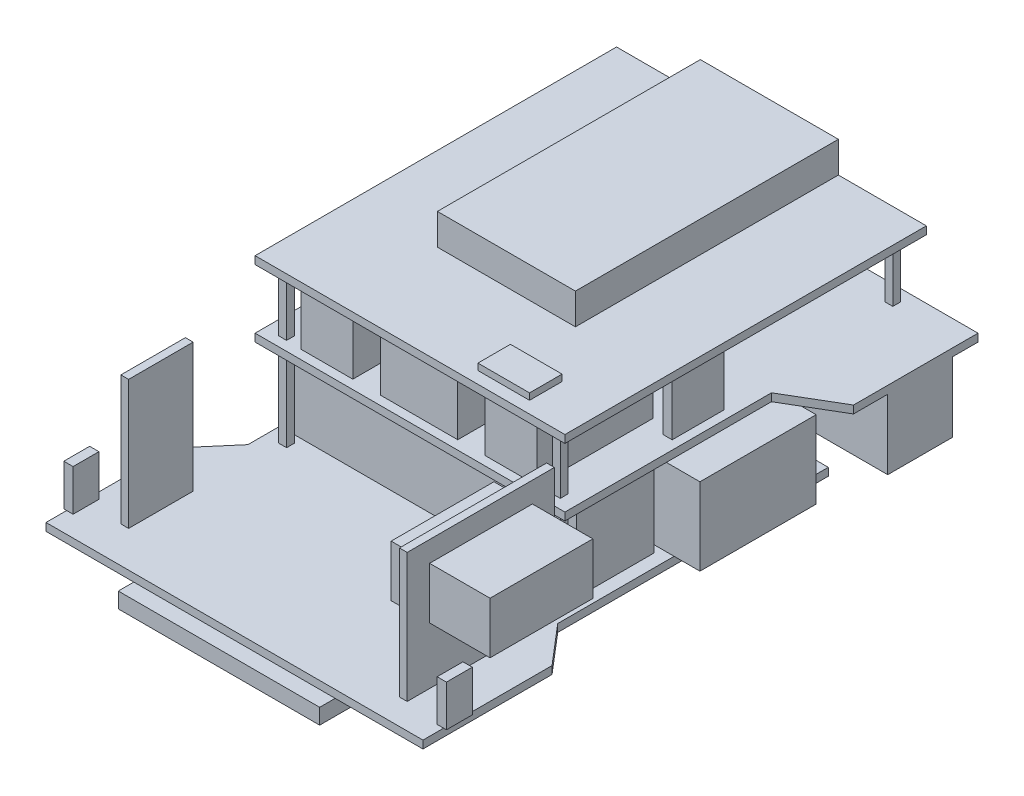
SolidWorks part; units mm, degrees
ref_plane "Front Plane" through (0, 0, 0) normal (0, 0, 1) x (1, 0, 0)
ref_plane "Top Plane" through (0, 0, 0) normal (0, 1, 0) x (1, 0, 0)
ref_plane "Right Plane" through (0, 0, 0) normal (1, 0, 0) x (0, 0, -1)
sketch "Sketch1" plane through (0, 0, 0) normal (0, 1, 0) x (1, 0, 0)
  line L0 (-73, -35) -> (-60, -19.8013)
  line L1 (60, -85) -> (-60, -85)
  line L2 (60, -19.8013) -> (60, 85)
  line L3 (60, 85) -> (-60, 85)
  line L4 (-60, -19.8013) -> (-60, 85)
  line L5 (60, -85) -> (-60, 85) construction
  line L6 (60, 85) -> (-60, -85) construction
  line L7 (0, 0) -> (0, -85) construction
  line L9 (-60, -85) -> (-73, -85)
  line L10 (-73, -35) -> (-73, -85)
  line L11 (60, -85) -> (73, -85)
  line L12 (73, -35) -> (73, -85)
  line L13 (73, -35) -> (60, -19.8013)
  point P0 (0, 0)
  dimension "D1" = 170
  dimension "D2" = 120
  dimension "D3" = 50
  dimension "D4" = 13
  dimension "D5" = 20
extrude "Boss-Extrude1" add sketch "Sketch1" along normal blind 3
sketch "Sketch2" plane through (0, 3, 0) normal (0, 1, 0) x (1, 0, 0)
  line L0 (0, 0) -> (0, 85) construction
  line L1 (60, 85) -> (-60, 85) construction
  line L2 (-60, 85) -> (-60, -19.8013) construction
  line L4 (-54.525, -13.335) -> (-51.475, -13.335)
  line L5 (-54.525, -13.335) -> (-54.525, -10.285)
  line L6 (-54.525, -10.285) -> (-51.475, -10.285)
  line L7 (-51.475, -13.335) -> (-51.475, -10.285)
  line L8 (-54.525, -13.335) -> (-51.475, -10.285) construction
  line L9 (-54.525, -10.285) -> (-51.475, -13.335) construction
  line L10 (51.475, -13.335) -> (54.525, -13.335)
  line L11 (51.475, -13.335) -> (51.475, -10.285)
  line L12 (51.475, -10.285) -> (54.525, -10.285)
  line L13 (54.525, -13.335) -> (54.525, -10.285)
  line L14 (51.475, -13.335) -> (54.525, -10.285) construction
  line L15 (51.475, -10.285) -> (54.525, -13.335) construction
  line L16 (52.475, 73.475) -> (55.525, 73.475)
  line L17 (52.475, 73.475) -> (52.475, 76.525)
  line L18 (52.475, 76.525) -> (55.525, 76.525)
  line L19 (55.525, 73.475) -> (55.525, 76.525)
  line L20 (52.475, 73.475) -> (55.525, 76.525) construction
  line L21 (52.475, 76.525) -> (55.525, 73.475) construction
  line L22 (-55.525, 73.475) -> (-52.475, 73.475)
  line L23 (-55.525, 73.475) -> (-55.525, 76.525)
  line L24 (-55.525, 76.525) -> (-52.475, 76.525)
  line L25 (-52.475, 73.475) -> (-52.475, 76.525)
  line L26 (-55.525, 73.475) -> (-52.475, 76.525) construction
  line L27 (-55.525, 76.525) -> (-52.475, 73.475) construction
  circle A0 centre (-53, -11.81) radius 1.525 construction
  circle A1 centre (-54, 75) radius 1.525 construction
  circle A2 centre (53, -11.81) radius 1.525 construction
  circle A3 centre (54, 75) radius 1.525 construction
  dimension "D1" = 10
  dimension "D2" = 3.05
  dimension "D3" = 6
  dimension "D4" = 3.05
  dimension "D5" = 7
  dimension "D6" = 86.81
extrude "Boss-Extrude2" add sketch "Sketch2" along normal blind 33
sketch "Sketch3" plane through (0, 36, 0) normal (0, 1, 0) x (1, 0, 0)
  line L0 (0, 52.99) -> (0, 122.99) construction
  line L1 (-60, -17.01) -> (60, -17.01)
  line L2 (-60, -17.01) -> (-60, 122.99)
  line L3 (-60, 122.99) -> (60, 122.99)
  line L4 (60, -17.01) -> (60, 122.99)
  line L5 (-60, -17.01) -> (60, 122.99) construction
  line L6 (-60, 122.99) -> (60, -17.01) construction
  line L7 (-60, 122.99) -> (-80, 122.99)
  line L8 (-80, 122.99) -> (-80, 74.7803)
  line L9 (-80, 74.7803) -> (-60, 62.99)
  line L10 (80, 74.7803) -> (60, 62.99)
  line L11 (80, 122.99) -> (80, 74.7803)
  line L12 (60, 122.99) -> (80, 122.99)
  line L14 (-54.525, -10.285) -> (-54.525, -13.335) construction
  point P0 (0, 52.99)
  point P5 (0, 0)
  point P15 (-80, 45.2902)
  point P16 (0, 0)
  point P19 (-54.525, -11.81)
  dimension "D1" = 120
  dimension "D2" = 140
  dimension "D3" = 60
  dimension "D4" = 30.52
  dimension "D5" = 20
  dimension "D6" = 5.2
extrude "Boss-Extrude3" add sketch "Sketch3" along normal blind 3 contours L8 L9 L2 L7 | L1 L4 L3 L2 | L12 L4 L10 L11
sketch "Sketch4" plane through (0, 39, 0) normal (0, 1, 0) x (1, 0, 0)
  line L0 (0, 0) -> (0, 32.3428) construction
  line L1 (-54.525, -13.335) -> (-51.475, -13.335)
  line L2 (-54.525, -13.335) -> (-54.525, -10.285)
  line L3 (-54.525, -10.285) -> (-51.475, -10.285)
  line L4 (-51.475, -13.335) -> (-51.475, -10.285)
  line L5 (-54.525, -13.335) -> (-51.475, -10.285) construction
  line L6 (-54.525, -10.285) -> (-51.475, -13.335) construction
  line L7 (-60, -17.01) -> (60, -17.01) construction
  line L8 (-60, -17.01) -> (-60, 62.99) construction
  line L9 (80, 122.99) -> (-80, 122.99) construction
  line L10 (-54.525, 115.465) -> (-51.475, 115.465)
  line L11 (-54.525, 115.465) -> (-54.525, 118.515)
  line L12 (-54.525, 118.515) -> (-51.475, 118.515)
  line L13 (-51.475, 115.465) -> (-51.475, 118.515)
  line L14 (-54.525, 115.465) -> (-51.475, 118.515) construction
  line L15 (-54.525, 118.515) -> (-51.475, 115.465) construction
  line L16 (54.525, -10.285) -> (51.475, -13.335) construction
  line L17 (54.525, -13.335) -> (51.475, -10.285) construction
  line L18 (51.475, -13.335) -> (51.475, -10.285)
  line L19 (54.525, -10.285) -> (51.475, -10.285)
  line L20 (54.525, -13.335) -> (54.525, -10.285)
  line L21 (54.525, -13.335) -> (51.475, -13.335)
  line L22 (54.525, 118.515) -> (51.475, 115.465) construction
  line L23 (54.525, 115.465) -> (51.475, 118.515) construction
  line L24 (51.475, 115.465) -> (51.475, 118.515)
  line L25 (54.525, 118.515) -> (51.475, 118.515)
  line L26 (54.525, 115.465) -> (54.525, 118.515)
  line L27 (54.525, 115.465) -> (51.475, 115.465)
  point P0 (-53, -11.81)
  point P12 (-53, 116.99)
  point P17 (0, 0)
  point P24 (53, -11.81)
  point P29 (53, 116.99)
  dimension "D1" = 3.05
  dimension "D2" = 5.2
  dimension "D3" = 7
  dimension "D4" = 6
extrude "Boss-Extrude4" add sketch "Sketch4" along normal blind 23
sketch "Sketch6" plane through (0, 62, 0) normal (0, 1, 0) x (1, 0, 0)
  line L0 (60, -17.01) -> (-60, -17.01)
  line L1 (60, -17.01) -> (60, 122.99)
  line L2 (-60, -17.01) -> (-60, 122.99)
  line L3 (60, 122.99) -> (-60, 122.99)
  line L4 (80, 122.99) -> (-80, 122.99) construction
extrude "Boss-Extrude5" add sketch "Sketch6" along normal blind 3
sketch "Sketch7" plane through (0, 36, 0) normal (0, -1, 0) x (1, 0, 0)
  line L0 (-80, -88.03) -> (-80, -113.03)
  line L1 (-80, -88.03) -> (-12, -88.03)
  line L2 (-80, -113.03) -> (-12, -113.03)
  line L3 (-12, -88.03) -> (-12, -113.03)
  line L4 (-80, -122.99) -> (-80, -74.7803) construction
  line L5 (0, 0) -> (0, -39.6137) construction
  line L6 (12, -88.03) -> (12, -113.03)
  line L7 (80, -113.03) -> (12, -113.03)
  line L8 (80, -88.03) -> (12, -88.03)
  line L9 (80, -88.03) -> (80, -113.03)
  line L10 (80, -122.99) -> (-80, -122.99) construction
  point P13 (-80, -100.53)
  dimension "D1" = 68
  dimension "D2" = 25
  dimension "D3" = 22.46
extrude "Boss-Extrude6" add sketch "Sketch7" along normal blind 27
sketch "Sketch9" plane through (0, 39, 0) normal (0, 1, 0) x (1, 0, 0)
  line L0 (-60, -17.01) -> (-60, 62.99) construction
  line L1 (-30.05, 55.88) -> (27.95, 55.88)
  line L2 (-30.05, 55.88) -> (-30.05, 115.88)
  line L3 (-30.05, 115.88) -> (27.95, 115.88)
  line L4 (27.95, 55.88) -> (27.95, 115.88)
  line L5 (-30.05, 55.88) -> (27.95, 115.88) construction
  line L6 (-30.05, 115.88) -> (27.95, 55.88) construction
  line L7 (80, 122.99) -> (-80, 122.99) construction
  line L8 (0, 0) -> (0, 23.7636) construction
  line L9 (-45.64, 31.48) -> (-25.64, 31.48)
  line L10 (-45.64, 31.48) -> (-45.64, -13.52)
  line L11 (-45.64, -13.52) -> (-25.64, -13.52)
  line L12 (-25.64, 31.48) -> (-25.64, -13.52)
  line L13 (-45.64, 31.48) -> (-25.64, -13.52) construction
  line L14 (-45.64, -13.52) -> (-25.64, 31.48) construction
  line L15 (-60, -17.01) -> (60, -17.01) construction
  line L16 (45.64, -13.52) -> (25.64, -13.52)
  line L17 (25.64, 31.48) -> (25.64, -13.52)
  line L18 (45.64, 31.48) -> (25.64, 31.48)
  line L19 (45.64, 31.48) -> (45.64, -13.52)
  line L21 (-15, 36.48) -> (15, 36.48)
  line L22 (-15, 36.48) -> (-15, -13.52)
  line L23 (-15, -13.52) -> (15, -13.52)
  line L24 (15, 36.48) -> (15, -13.52)
  line L25 (-15, 36.48) -> (15, -13.52) construction
  line L26 (-15, -13.52) -> (15, 36.48) construction
  point P0 (-1.05, 85.88)
  point P9 (-35.64, 8.98)
  point P23 (0, 11.48)
  point P28 (0, 14.4115)
  dimension "D1" = 58
  dimension "D2" = 29.95
  dimension "D3" = 60
  dimension "D4" = 7.11
  dimension "D5" = 20
  dimension "D6" = 45
  dimension "D7" = 3.49
  dimension "D8" = 14.36
  dimension "D9" = 3.49
  dimension "D10" = 30
  dimension "D11" = 50
extrude "Boss-Extrude7" add sketch "Sketch9" along normal blind 20
sketch "Sketch10" plane through (0, 65, 0) normal (0, 1, 0) x (1, 0, 0)
  line L0 (-27.54, 122.99) -> (25.92, 122.99)
  line L1 (-27.54, 122.99) -> (-27.54, 21.14)
  line L2 (25.92, 122.99) -> (25.92, 21.14)
  line L3 (-27.54, 21.14) -> (25.92, 21.14)
  line L4 (60, 122.99) -> (-60, 122.99) construction
  line L5 (-60, 122.99) -> (-60, -17.01) construction
  dimension "D1" = 32.46
  dimension "D2" = 53.46
  dimension "D3" = 101.85
extrude "Boss-Extrude8" add sketch "Sketch10" along normal blind 12
sketch "Sketch11" plane through (0, 3, 0) normal (0, 1, 0) x (1, 0, 0)
  line L1 (-55, 22.5437) -> (55, 22.5437)
  line L2 (-55, 22.5437) -> (-55, -7.4563)
  line L3 (-55, -7.4563) -> (55, -7.4563)
  line L4 (55, 22.5437) -> (55, -7.4563)
  line L5 (-55, 22.5437) -> (55, -7.4563) construction
  line L6 (-55, -7.4563) -> (55, 22.5437) construction
  point P0 (0, 7.5437)
  point P5 (0, 0)
  dimension "D1" = 110
  dimension "D2" = 30
extrude "Boss-Extrude9" add sketch "Sketch11" along normal blind 32
sketch "Sketch12" plane through (0, 3, 0) normal (0, 1, 0) x (1, 0, 0)
  line L1 (-70, 25.2932) -> (70, 25.2932)
  line L2 (-70, 25.2932) -> (-70, 70.2932)
  line L3 (-70, 70.2932) -> (70, 70.2932)
  line L4 (70, 25.2932) -> (70, 70.2932)
  line L5 (-70, 25.2932) -> (70, 70.2932) construction
  line L6 (-70, 70.2932) -> (70, 25.2932) construction
  point P0 (0, 47.7932)
  point P5 (0, 0)
  point P7 (-0.81, 39.9421)
  point P8 (0, 47.7932)
  dimension "D1" = 140
  dimension "D2" = 45
extrude "Boss-Extrude10" add sketch "Sketch12" along normal blind 30
sketch "Sketch13" plane through (0, 65, 0) normal (0, 1, 0) x (1, 0, 0)
  line L0 (60, -17.01) -> (60, 122.99) construction
  line L1 (21.68, -12.39) -> (41.68, -12.39)
  line L2 (21.68, -12.39) -> (21.68, 0.21)
  line L3 (21.68, 0.21) -> (41.68, 0.21)
  line L4 (41.68, -12.39) -> (41.68, 0.21)
  line L5 (21.68, -12.39) -> (41.68, 0.21) construction
  line L6 (21.68, 0.21) -> (41.68, -12.39) construction
  line L7 (-60, -17.01) -> (60, -17.01) construction
  point P0 (31.68, -6.09)
  dimension "D1" = 20
  dimension "D2" = 12.6
  dimension "D3" = 18.32
  dimension "D4" = 4.62
extrude "Boss-Extrude11" add sketch "Sketch13" along normal blind 2.5
sketch "Sketch14" plane through (0, 39, 0) normal (0, 1, 0) x (1, 0, 0)
  line L0 (60, -17.01) -> (60, 122.99) construction
  line L1 (56.55, 47.99) -> (52.95, 47.99)
  line L2 (56.55, 47.99) -> (56.55, 27.99)
  line L3 (56.55, 27.99) -> (52.95, 27.99)
  line L4 (52.95, 47.99) -> (52.95, 27.99)
  line L5 (56.55, 47.99) -> (52.95, 27.99) construction
  line L6 (56.55, 27.99) -> (52.95, 47.99) construction
  line L7 (-60, -17.01) -> (60, -17.01) construction
  line L8 (0, 0) -> (0, 51.8866) construction
  line L9 (-56.55, 27.99) -> (-52.95, 47.99) construction
  line L10 (-56.55, 47.99) -> (-52.95, 27.99) construction
  line L11 (-52.95, 47.99) -> (-52.95, 27.99)
  line L12 (-56.55, 27.99) -> (-52.95, 27.99)
  line L13 (-56.55, 47.99) -> (-56.55, 27.99)
  line L14 (-56.55, 47.99) -> (-52.95, 47.99)
  point P0 (54.75, 37.99)
  point P16 (-54.75, 37.99)
  dimension "D1" = 3.45
  dimension "D2" = 7.05
  dimension "D3" = 20
  dimension "D4" = 45
extrude "Boss-Extrude12" add sketch "Sketch14" along normal blind 20
sketch "Sketch15" plane through (0, 3, 0) normal (0, 1, 0) x (1, 0, 0)
  line L0 (73, -85) -> (73, -35) construction
  line L1 (70.5, -67) -> (74.1, -67)
  line L2 (70.5, -67) -> (70.5, -77)
  line L3 (70.5, -77) -> (74.1, -77)
  line L4 (74.1, -67) -> (74.1, -77)
  line L5 (-73, -85) -> (73, -85) construction
  line L6 (0, 0) -> (0, -32.3725) construction
  line L7 (-70.5, -67) -> (-74.1, -67)
  line L8 (-74.1, -67) -> (-74.1, -77)
  line L9 (-70.5, -77) -> (-74.1, -77)
  line L10 (-70.5, -67) -> (-70.5, -77)
  dimension "D1" = 1.1
  dimension "D2" = 2.5
  dimension "D3" = 10
  dimension "D4" = 8
extrude "Boss-Extrude13" add sketch "Sketch15" along normal blind 16
sketch "Sketch16" plane through (0, 3, 0) normal (0, 1, 0) x (1, 0, 0)
  line L0 (73, -67) -> (73, -35) construction
  line L1 (54, -18.1) -> (57, -18.1)
  line L2 (54, -18.1) -> (54, -75.1)
  line L3 (54, -75.1) -> (57, -75.1)
  line L4 (57, -18.1) -> (57, -75.1)
  line L5 (-73, -85) -> (73, -85) construction
  line L6 (-73, -35) -> (-73, -67) construction
  line L7 (-58, -46) -> (-55, -46)
  line L8 (-58, -46) -> (-58, -71)
  line L9 (-58, -71) -> (-55, -71)
  line L10 (-55, -46) -> (-55, -71)
  dimension "D1" = 19
  dimension "D2" = 3
  dimension "D3" = 57
  dimension "D4" = 9.9
  dimension "D5" = 15
  dimension "D6" = 3
  dimension "D7" = 25
  dimension "D8" = 14
extrude "Boss-Extrude14" add sketch "Sketch16" along normal blind 50
sketch "Sketch17" plane through (57, 0, 0) normal (1, 0, 0) x (0, 0, -1)
  line L0 (-75.1, 53) -> (-18.1, 53) construction
  line L1 (-66.4113, 45) -> (-26.6028, 45)
  line L2 (-66.4113, 45) -> (-66.4113, 25)
  line L3 (-66.4113, 25) -> (-26.6028, 25)
  line L4 (-26.6028, 45) -> (-26.6028, 25)
  dimension "D1" = 8
  dimension "D2" = 20
extrude "Boss-Extrude15" add sketch "Sketch17" along normal blind 23.4 and the other way blind 14.9
sketch "Sketch18" plane through (0, 0, 0) normal (0, -1, 0) x (1, 0, 0)
  line L0 (-73, 85) -> (73, 85) construction
  line L1 (-39, 66) -> (39, 66)
  line L2 (-39, 66) -> (-39, 91)
  line L3 (-39, 91) -> (39, 91)
  line L4 (39, 66) -> (39, 91)
  point P4 (0, 66)
  dimension "D1" = 25
  dimension "D2" = 78
  dimension "D3" = 6
extrude "Boss-Extrude16" add sketch "Sketch18" along normal blind 6
